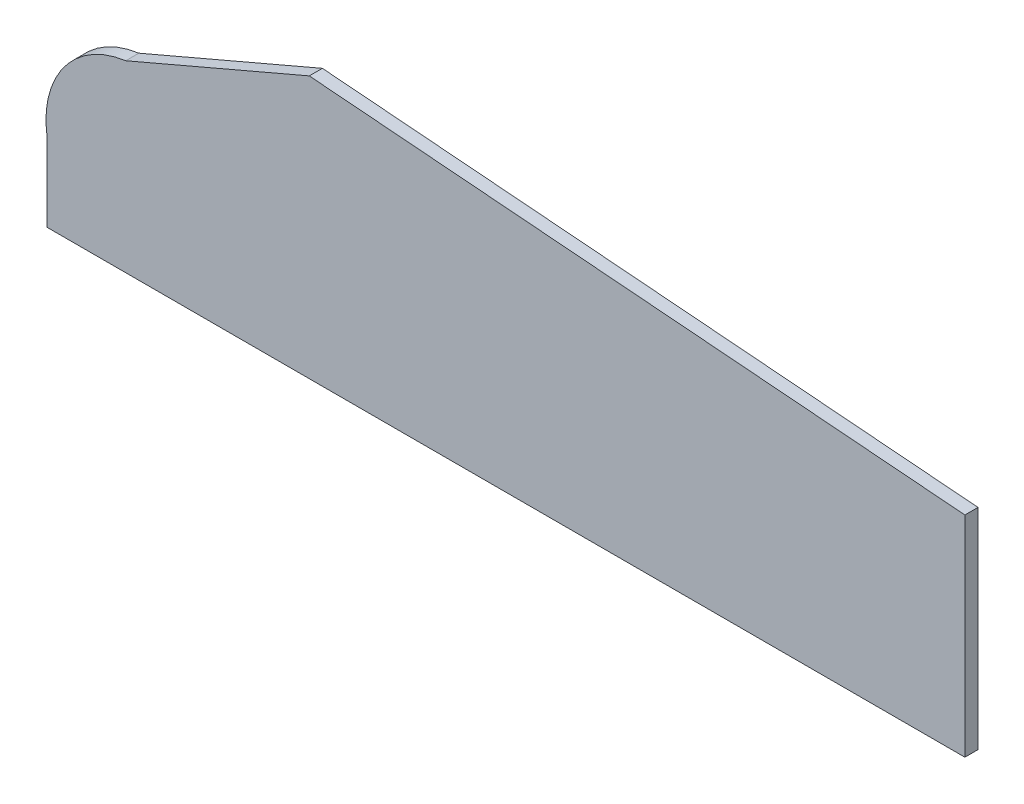
SolidWorks part; units mm, degrees
ref_plane "Plan de face" through (0, 0, 0) normal (0, 0, 1) x (1, 0, 0)
ref_plane "Plan de dessus" through (0, 0, 0) normal (0, 1, 0) x (1, 0, 0)
ref_plane "Plan de droite" through (0, 0, 0) normal (1, 0, 0) x (0, 0, -1)
sketch "Esquisse1" plane through (0, 0, 0) normal (0, 0, 1) x (1, 0, 0)
  line L0 (0, 0) -> (350, 0)
  line L1 (350, 0) -> (350, 80)
  line L2 (350, 80) -> (100, 100)
  line L3 (100, 100) -> (30, 70)
  line L4 (0, 0) -> (0, 30)
  arc A1 (30, 70) -> (0, 30) centre (34.5959, 35.3031) ccw
extrude "Boss.-Extru.1" add sketch "Esquisse1" along normal blind 5
